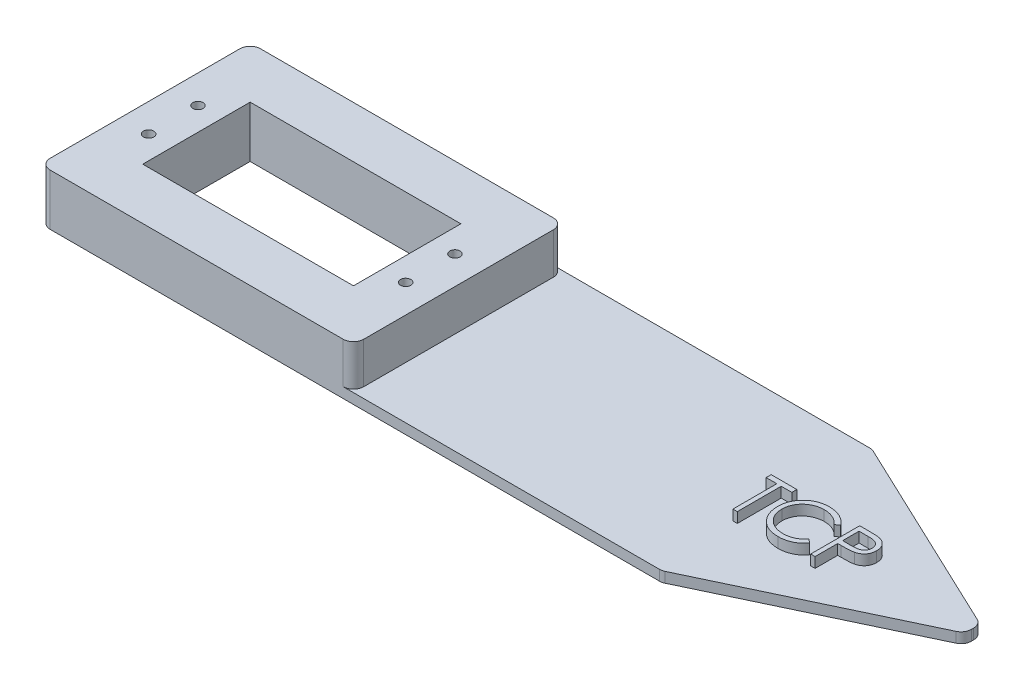
SolidWorks part; units mm, degrees
ref_plane "Front Plane" through (0, 0, 0) normal (0, 0, 1) x (1, 0, 0)
ref_plane "Top Plane" through (0, 0, 0) normal (0, 1, 0) x (1, 0, 0)
ref_plane "Right Plane" through (0, 0, 0) normal (1, 0, 0) x (0, 0, -1)
sketch "Sketch1" plane through (0, 0, 0) normal (0, 1, 0) x (1, 0, 0)
  line L0 (-20.5, -10.45) -> (-20.5, 10.45)
  line L1 (-30.5, -20.45) -> (30.5, -20.45)
  line L2 (-30.5, -20.45) -> (-30.5, 20.45)
  line L3 (-30.5, 20.45) -> (30.5, 20.45)
  line L4 (30.5, -20.45) -> (30.5, 20.45)
  line L5 (-30.5, -20.45) -> (30.5, 20.45) construction
  line L6 (-30.5, 20.45) -> (30.5, -20.45) construction
  line L7 (-20.5, 10.45) -> (20.5, 10.45)
  line L8 (20.5, -10.45) -> (20.5, 10.45)
  line L9 (-20.5, -10.45) -> (20.5, -10.45)
  line L10 (0.2151, 0) -> (10.5374, 0) construction
  line L11 (0, 0) -> (0, 7.1707) construction
  circle A0 centre (25, 4.8) radius 1
  circle A1 centre (-25, 4.8) radius 1
  circle A2 centre (25, -4.8) radius 1
  circle A3 centre (-25, -4.8) radius 1
  point P0 (0, 0)
  dimension "D4" = 2
  dimension "D5" = 4.8
  dimension "D6" = 5.5
  dimension "D1" = 61
  dimension "D2" = 40.9
  dimension "D3" = 10
extrude "Boss-Extrude1" add sketch "Sketch1" along normal blind 10
sketch "Sketch3" plane through (30.5, 0, 0) normal (1, 0, 0) x (0, 0, -1)
  line L0 (20.45, 10) -> (20.45, 0) construction
  line L1 (-20.45, 0) -> (20.45, 0)
  line L2 (-20.45, 0) -> (-20.45, 2)
  line L3 (-20.45, 2) -> (20.45, 2)
  line L4 (20.45, 0) -> (20.45, 2)
  dimension "D1" = 2
extrude "Boss-Extrude2" add sketch "Sketch3" along normal blind 100
fillet "Fillet1" radius 2 4 edges at (30.5, 6, -20.45) (30.5, 6, 20.45) (-30.5, 5, -20.45) (-30.5, 5, 20.45)
sketch "Sketch4" plane through (0, 2, 0) normal (0, 1, 0) x (1, 0, 0)
  line L0 (130.5, -1.5) -> (90.5, -20.45)
  line L1 (90.5, -20.45) -> (130.5, -20.45)
  line L2 (130.5, -20.45) -> (28.5, -20.45) construction
  line L3 (130.5, 20.45) -> (130.5, -20.45) construction
  line L4 (130.5, -1.5) -> (130.5, 0) construction
  line L5 (130.5, 0) -> (99.7105, 0) construction
  line L6 (130.5, -20.45) -> (130.5, -1.5)
  line L7 (130.5, 20.45) -> (130.5, 1.5)
  line L8 (90.5, 20.45) -> (130.5, 20.45)
  line L9 (130.5, 1.5) -> (90.5, 20.45)
  point P9 (130.5, 0)
  dimension "D1" = 40
  dimension "D2" = 1.5
extrude "Cut-Extrude1" cut sketch "Sketch4" against normal up to next
fillet "Fillet2" radius 2 4 edges at (90.5, 1, -20.45) (130.5, 1, -1.5) (130.5, 1, 1.5) (90.5, 1, 20.45)
sketch "Sketch5" plane through (0, 2, 0) normal (0, 1, 0) x (1, 0, 0)
  text T0 "TCP" font "Century Gothic" height in points 36
extrude "Boss-Extrude3" add sketch "Sketch5" along normal blind 2
